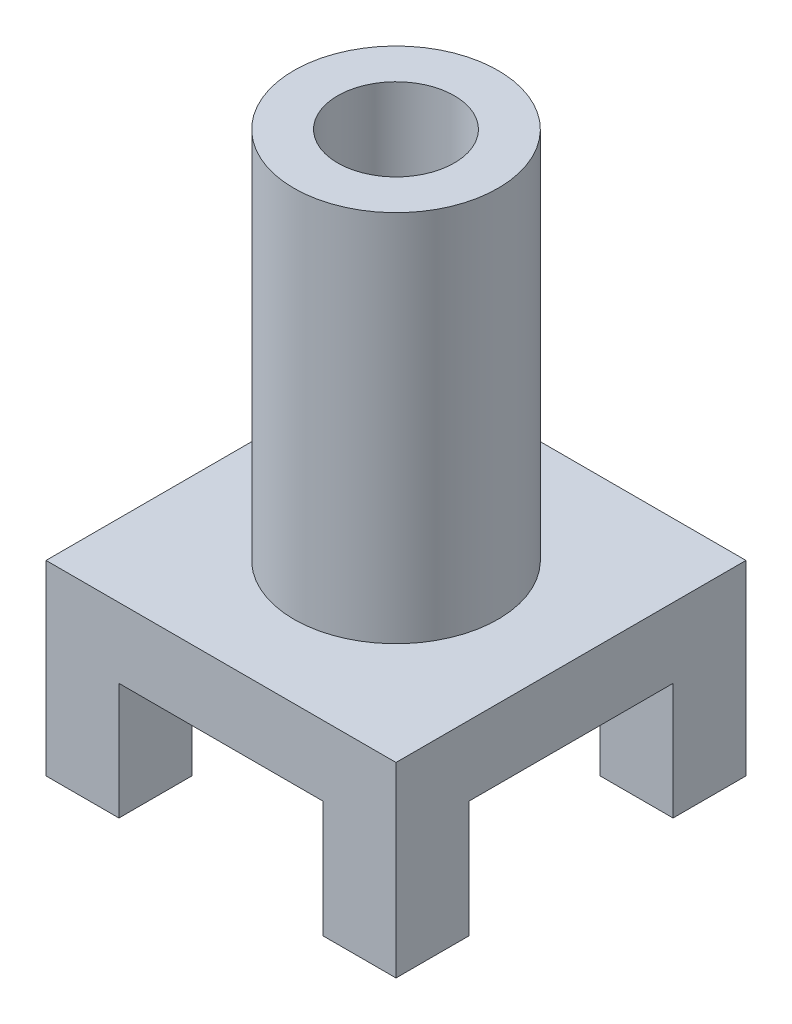
SolidWorks part; units mm, degrees
ref_plane "Front Plane" through (0, 0, 0) normal (0, 0, 1) x (1, 0, 0)
ref_plane "Top Plane" through (0, 0, 0) normal (0, 1, 0) x (1, 0, 0)
ref_plane "Right Plane" through (0, 0, 0) normal (1, 0, 0) x (0, 0, -1)
sketch "Sketch1" plane through (0, 0, 0) normal (0, 1, 0) x (1, 0, 0)
  line L1 (-30, -30) -> (30, -30)
  line L2 (-30, -30) -> (-30, 30)
  line L3 (-30, 30) -> (30, 30)
  line L4 (30, -30) -> (30, 30)
  line L5 (-30, -30) -> (30, 30) construction
  line L6 (-30, 30) -> (30, -30) construction
  point P0 (0, 0)
  point P6 (0, 0)
  dimension "D1" = 60
  dimension "D2" = 60
extrude "Boss-Extrude1" add sketch "Sketch1" along normal blind 32 contours L2 L1 L4 L3
sketch "Sketch2" plane through (30, 0, 0) normal (1, 0, 0) x (0, 0, -1)
  line L0 (-30, 0) -> (30, 0) construction
  line L1 (-17.5, 0) -> (17.5, 0)
  line L2 (-17.5, 0) -> (-17.5, 20)
  line L3 (-17.5, 20) -> (17.5, 20)
  line L4 (17.5, 0) -> (17.5, 20)
  dimension "D1" = 35
  dimension "D2" = 20
  dimension "D3" = 17.5
extrude "Cut-Extrude2" cut sketch "Sketch2" against normal through all contours L2 L1 L4 L3
sketch "Sketch4" plane through (0, 0, 30) normal (0, 0, 1) x (1, 0, 0)
  line L0 (-30, 0) -> (30, 0) construction
  line L1 (-17.5, 0) -> (17.5, 0)
  line L2 (-17.5, 0) -> (-17.5, 20)
  line L3 (-17.5, 20) -> (17.5, 20)
  line L4 (17.5, 0) -> (17.5, 20)
  dimension "D1" = 35
  dimension "D2" = 20
  dimension "D3" = 17.5
extrude "Cut-Extrude3" cut sketch "Sketch4" against normal through all contours L2 L1 L4 L3
sketch "Sketch5" plane through (0, 32, 0) normal (0, 1, 0) x (1, 0, 0)
  circle A0 centre (0, 0) radius 17.5
  dimension "D1" = 35
extrude "Boss-Extrude2" add sketch "Sketch5" along normal blind 64 contours A0
sketch "Sketch6" plane through (0, 96, 0) normal (0, 1, 0) x (1, 0, 0)
  circle A0 centre (0, 0) radius 10
  dimension "D1" = 20
extrude "Cut-Extrude4" cut sketch "Sketch6" against normal through all
